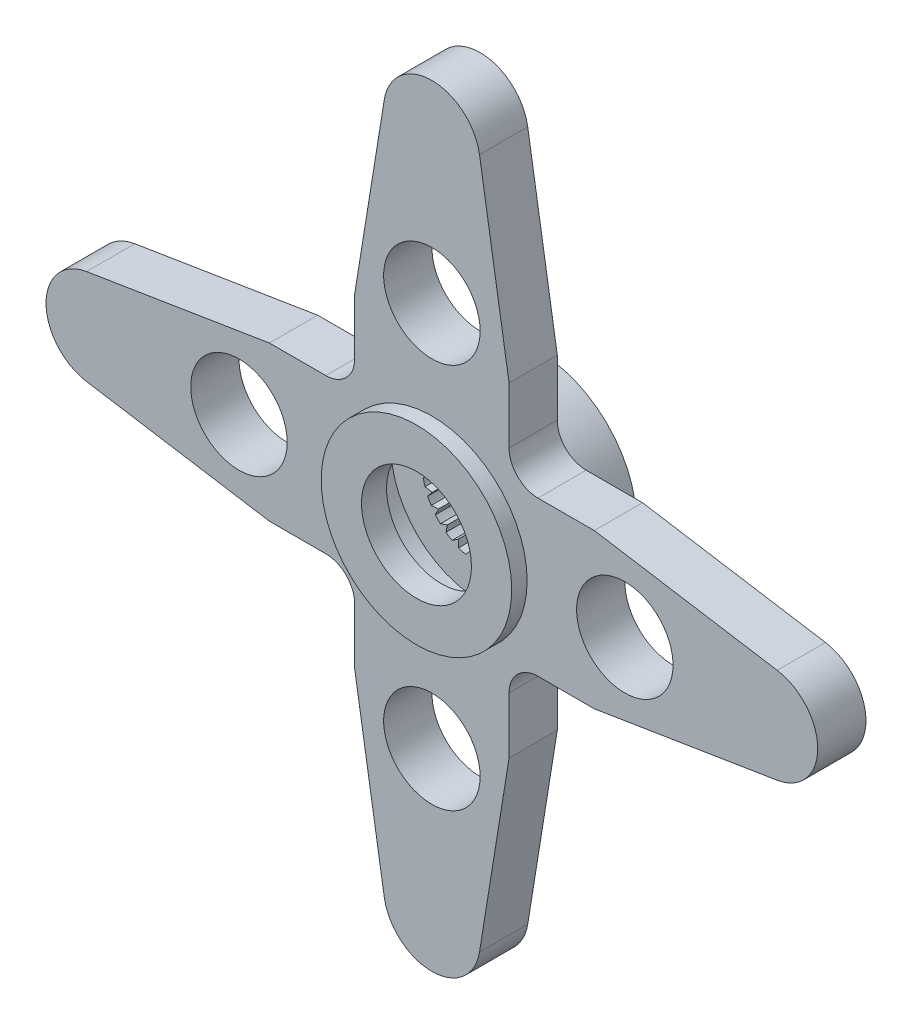
SolidWorks part; units mm, degrees
ref_plane "Front Plane" through (0, 0, 0) normal (0, 0, 1) x (1, 0, 0)
ref_plane "Top Plane" through (0, 0, 0) normal (0, 1, 0) x (1, 0, 0)
ref_plane "Right Plane" through (0, 0, 0) normal (1, 0, 0) x (0, 0, -1)
ref_plane "Plane1" through (0, 0, 2.5) normal (0, 0, 1) x (1, 0, 0)
sketch "Sketch1" plane through (0, 0, 2.5) normal (0, 0, 1) x (1, 0, 0)
  line L0 (4, -8.4192) -> (4, -4)
  line L1 (4, -4) -> (8.4192, -4)
  line L2 (8.4192, -4) -> (17.8989, -2.468)
  line L3 (17.8989, 2.468) -> (8.4192, 4)
  line L4 (8.4192, 4) -> (4, 4)
  line L5 (4, 4) -> (4, 8.4192)
  line L6 (4, 8.4192) -> (2.468, 17.8989)
  line L7 (-2.468, 17.8989) -> (-4, 8.4192)
  line L8 (-4, 8.4192) -> (-4, 4)
  line L9 (-4, 4) -> (-8.4192, 4)
  line L10 (-8.4192, 4) -> (-17.8989, 2.468)
  line L11 (-17.8989, -2.468) -> (-8.4192, -4)
  line L12 (-8.4192, -4) -> (-4, -4)
  line L13 (-4, -4) -> (-4, -8.4192)
  line L14 (-4, -8.4192) -> (-2.468, -17.8989)
  line L15 (2.468, -17.8989) -> (4, -8.4192)
  arc A0 (17.8989, -2.468) -> (17.8989, 2.468) centre (17.5, 0) ccw
  arc A1 (2.468, 17.8989) -> (-2.468, 17.8989) centre (0, 17.5) ccw
  arc A2 (-17.8989, 2.468) -> (-17.8989, -2.468) centre (-17.5, 0) ccw
  arc A3 (-2.468, -17.8989) -> (2.468, -17.8989) centre (0, -17.5) ccw
extrude "Boss-Extrude1" add sketch "Sketch1" against normal blind 2.5
hole_wizard "M8 Clearance Hole1" positions "Sketch3" profile "Sketch2" hole size "M8" standard "ANSI Metric"
sketch "Sketch3" plane through (0, 0, 2.5) normal (0, 0, 1) x (1, 0, 0)
  point P0 (0, 0)
sketch "Sketch2" plane through (0, 0, 2.5) normal (1, 0, 0) x (0, -1, 0)
  line L0 (0, 0) -> (0, 2.5)
  line L1 (0, 2.5) -> (4.625, 2.5)
  line L2 (4.625, 2.5) -> (4.625, 0)
  line L5 (4.625, 0) -> (0, 0)
  line L11 (0, -6.35) -> (0, 107.95) construction
  dimension "Thru Hole Dia." = 9.25
  dimension "Thru Hole Depth" = 2.5
ref_plane "Plane2" through (0, 0, 2) normal (0, 0, -1) x (-1, 0, 0)
sketch "Sketch4" plane through (0, 0, 2) normal (0, 0, -1) x (-1, 0, 0)
  circle A0 centre (0, 0) radius 4.938
extrude "Boss-Extrude2" add sketch "Sketch4" against normal blind 1.3
sketch "Sketch5" plane through (0, 0, 0) normal (0, 0, 1) x (1, 0, 0)
  circle A0 centre (0, 0) radius 5.0996
extrude "Boss-Extrude3" add sketch "Sketch5" against normal blind 3
sketch "Sketch6" plane through (0, 0, -3) normal (0, 0, -1) x (-1, 0, 0)
  line L0 (-2.9946, 0.1807) -> (-2.6675, 0)
  line L1 (-2.6675, 0) -> (-2.9936, -0.1964)
  line L2 (-2.9454, -0.5697) -> (-2.5837, -0.6634)
  line L3 (-2.5837, -0.6634) -> (-2.8507, -0.9347)
  line L4 (-2.7112, -1.2843) -> (-2.3375, -1.2851)
  line L5 (-2.3375, -1.2851) -> (-2.5287, -1.6143)
  line L6 (-2.3066, -1.9182) -> (-1.9445, -1.826)
  line L7 (-1.9445, -1.826) -> (-2.0478, -2.1924)
  line L8 (-1.7571, -2.4316) -> (-1.4293, -2.2522)
  line L9 (-1.4293, -2.2522) -> (-1.4382, -2.6328)
  line L10 (-1.0972, -2.7922) -> (-0.8243, -2.5369)
  line L11 (-0.8243, -2.5369) -> (-0.7383, -2.9077)
  line L12 (-0.3683, -2.9773) -> (-0.1675, -2.6622)
  line L13 (-0.1675, -2.6622) -> (0.0081, -3)
  line L14 (0.3837, -2.9754) -> (0.4998, -2.6202)
  line L15 (0.4998, -2.6202) -> (0.7539, -2.9037)
  line L16 (1.1115, -2.7865) -> (1.1358, -2.4136)
  line L17 (1.1358, -2.4136) -> (1.4523, -2.625)
  line L18 (1.7696, -2.4225) -> (1.7003, -2.0553)
  line L19 (1.7003, -2.0553) -> (2.0595, -2.1814)
  line L20 (2.3164, -1.9063) -> (2.158, -1.5679)
  line L21 (2.158, -1.5679) -> (2.5373, -1.6007)
  line L22 (2.7178, -1.2704) -> (2.4802, -0.982)
  line L23 (2.4802, -0.982) -> (2.8556, -0.9194)
  line L24 (2.9483, -0.5546) -> (2.6464, -0.3343)
  line L25 (2.6464, -0.3343) -> (2.9946, -0.1803)
  line L26 (2.9936, 0.1961) -> (2.6464, 0.3343)
  line L27 (2.6464, 0.3343) -> (2.9453, 0.5701)
  line L28 (2.8508, 0.9344) -> (2.4802, 0.982)
  line L29 (2.4802, 0.982) -> (2.711, 1.2846)
  line L30 (2.5288, 1.614) -> (2.158, 1.5679)
  line L31 (2.158, 1.5679) -> (2.3064, 1.9185)
  line L32 (2.048, 2.1922) -> (1.7003, 2.0553)
  line L33 (1.7003, 2.0553) -> (1.7568, 2.4318)
  line L34 (1.4385, 2.6326) -> (1.1358, 2.4136)
  line L35 (1.1358, 2.4136) -> (1.0969, 2.7923)
  line L36 (0.7386, 2.9077) -> (0.4998, 2.6202)
  line L37 (0.4998, 2.6202) -> (0.368, 2.9773)
  line L38 (-0.0077, 3) -> (-0.1675, 2.6622)
  line L39 (-0.1675, 2.6622) -> (-0.384, 2.9753)
  line L40 (-0.7535, 2.9038) -> (-0.8243, 2.5369)
  line L41 (-0.8243, 2.5369) -> (-1.1119, 2.7864)
  line L42 (-1.452, 2.6252) -> (-1.4293, 2.2522)
  line L43 (-1.4293, 2.2522) -> (-1.7699, 2.4223)
  line L44 (-2.0593, 2.1816) -> (-1.9445, 1.826)
  line L45 (-1.9445, 1.826) -> (-2.3167, 1.9061)
  line L46 (-2.5371, 1.601) -> (-2.3375, 1.2851)
  line L47 (-2.3375, 1.2851) -> (-2.7179, 1.27)
  line L48 (-2.8555, 0.9197) -> (-2.5837, 0.6634)
  line L49 (-2.5837, 0.6634) -> (-2.9484, 0.5542)
  arc A0 (-2.9936, -0.1964) -> (-2.9454, -0.5697) centre (0, 0) ccw
  arc A1 (-2.8507, -0.9347) -> (-2.7112, -1.2843) centre (0, 0) ccw
  arc A2 (-2.5287, -1.6143) -> (-2.3066, -1.9182) centre (0, 0) ccw
  arc A3 (-2.0478, -2.1924) -> (-1.7571, -2.4316) centre (0, 0) ccw
  arc A4 (-1.4382, -2.6328) -> (-1.0972, -2.7922) centre (0, 0) ccw
  arc A5 (-0.7383, -2.9077) -> (-0.3683, -2.9773) centre (0, 0) ccw
  arc A6 (0.0081, -3) -> (0.3837, -2.9754) centre (0, 0) ccw
  arc A7 (0.7539, -2.9037) -> (1.1115, -2.7865) centre (0, 0) ccw
  arc A8 (1.4523, -2.625) -> (1.7696, -2.4225) centre (0, 0) ccw
  arc A9 (2.0595, -2.1814) -> (2.3164, -1.9063) centre (0, 0) ccw
  arc A10 (2.5373, -1.6007) -> (2.7178, -1.2704) centre (0, 0) ccw
  arc A11 (2.8556, -0.9194) -> (2.9483, -0.5546) centre (0, 0) ccw
  arc A12 (2.9946, -0.1803) -> (2.9936, 0.1961) centre (0, 0) ccw
  arc A13 (2.9453, 0.5701) -> (2.8508, 0.9344) centre (0, 0) ccw
  arc A14 (2.711, 1.2846) -> (2.5288, 1.614) centre (0, 0) ccw
  arc A15 (2.3064, 1.9185) -> (2.048, 2.1922) centre (0, 0) ccw
  arc A16 (1.7568, 2.4318) -> (1.4385, 2.6326) centre (0, 0) ccw
  arc A17 (1.0969, 2.7923) -> (0.7386, 2.9077) centre (0, 0) ccw
  arc A18 (0.368, 2.9773) -> (-0.0077, 3) centre (0, 0) ccw
  arc A19 (-0.384, 2.9753) -> (-0.7535, 2.9038) centre (0, 0) ccw
  arc A20 (-1.1119, 2.7864) -> (-1.452, 2.6252) centre (0, 0) ccw
  arc A21 (-1.7699, 2.4223) -> (-2.0593, 2.1816) centre (0, 0) ccw
  arc A22 (-2.3167, 1.9061) -> (-2.5371, 1.601) centre (0, 0) ccw
  arc A23 (-2.7179, 1.27) -> (-2.8555, 0.9197) centre (0, 0) ccw
  arc A24 (-2.9484, 0.5542) -> (-2.9946, 0.1807) centre (0, 0) ccw
extrude "Cut-Extrude1" cut sketch "Sketch6" against normal blind 3.6
hole_wizard "CBORE for M2.5 Hex Head Machine Screw1" positions "Sketch10" profile "Sketch9" counterbore size "M2.5" standard "ANSI Metric"
sketch "Sketch10" plane through (0, 0, 3.3) normal (0, 0, 1) x (1, 0, 0)
  point P0 (0, 0)
sketch "Sketch9" plane through (0, 0, 3.3) normal (1, 0, 0) x (0, -1, 0)
  line L0 (0, 0) -> (0, 1.3)
  line L1 (0, 1.3) -> (1.5, 1.3)
  line L3 (1.5, 1.3) -> (1.5, 1.5)
  line L4 (1.5, 1.5) -> (2.85, 1.5)
  line L5 (2.85, 1.5) -> (2.85, 0)
  line L7 (2.85, 0) -> (0, 0)
  line L11 (0, -6.35) -> (0, 107.95) construction
  dimension "Thru Hole Dia." = 3
  dimension "Thru Hole Depth" = 1.3
  dimension "C'Bore Dia." = 5.7
  dimension "C'Bore Depth" = 1.5
ref_plane "Plane3" through (0, 0, 0) normal (0.7071, 0.7071, 0) x (-0.7071, 0.7071, 0)
ref_plane "Plane4" through (0, 0, 0) normal (-0.7071, -0.7071, 0) x (0.7071, -0.7071, 0)
ref_plane "Plane5" through (0, 0, 0) normal (-0.7071, 0.7071, 0) x (-0.7071, -0.7071, 0)
ref_plane "Plane6" through (0, 0, 0) normal (0.7071, -0.7071, 0) x (0.7071, 0.7071, 0)
ref_plane "Plane7" through (0, 0, 0) normal (-1, 0, 0) x (0, -1, 0)
ref_plane "Plane8" through (0, 0, 0) normal (0, -1, 0) x (1, 0, 0)
fillet "Fillet1" radius 1.5 4 edges at (4, -4, 1.25) (-4, -4, 1.25) (-4, 4, 1.25) (4, 4, 1.25)
sketch "Sketch11" plane through (0, 0, 2.5) normal (0, 0, 1) x (1, 0, 0)
  line L0 (0, 0) -> (0, 10) construction
  circle A0 centre (0, 10) radius 2.5
  circle A1 centre (10, 0) radius 2.5
  circle A2 centre (0, -10) radius 2.5
  circle A3 centre (-10, 0) radius 2.5
  point P13 (0, 0)
  dimension "D2" = 5
  dimension "D1" = 10
  dimension "D3" = 4
extrude "Cut-Extrude2" cut sketch "Sketch11" against normal blind 10 contours A3 | A1 | A2 | A0
